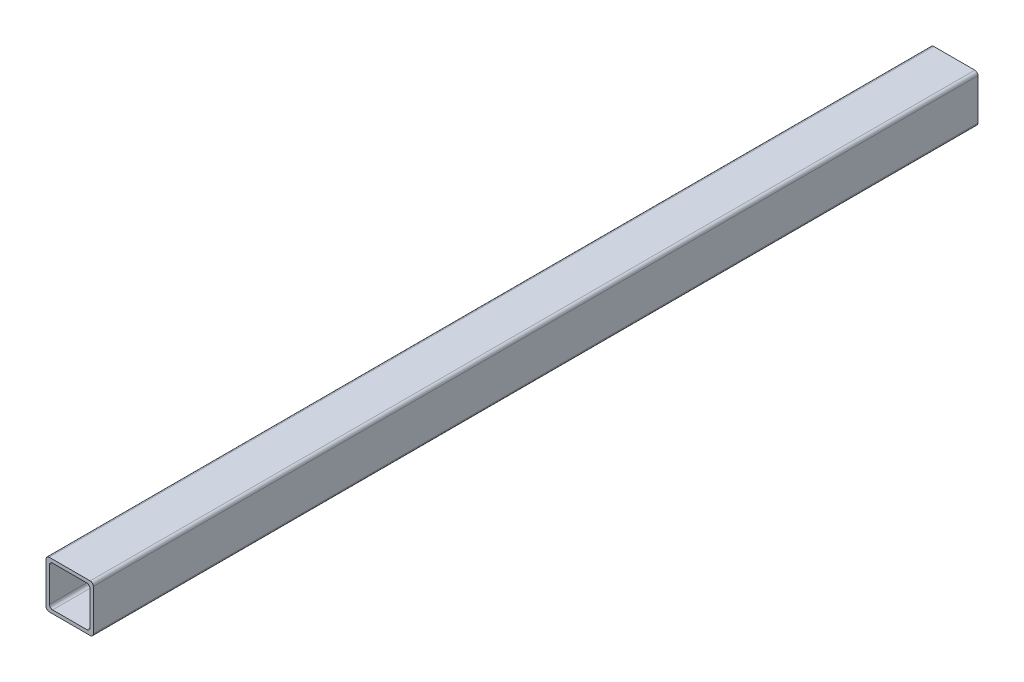
SolidWorks part; units mm, degrees
material "ASTM A500 Grade B"
ref_plane "Front Plane" through (0, 0, 0) normal (0, 0, 1) x (1, 0, 0)
ref_plane "Top Plane" through (0, 0, 0) normal (0, 1, 0) x (1, 0, 0)
ref_plane "Right Plane" through (0, 0, 0) normal (1, 0, 0) x (0, 0, -1)
sketch "Sketch1" plane through (0, 0, 0) normal (0, 0, 1) x (1, 0, 0)
  line L0 (5.3086, -2.7686) -> (32.7914, -2.7686)
  line L1 (2.54, 0) -> (35.56, 0)
  line L2 (0, -2.54) -> (0, -35.56)
  line L3 (2.54, -38.1) -> (35.56, -38.1)
  line L4 (38.1, -2.54) -> (38.1, -35.56)
  line L5 (35.3314, -5.3086) -> (35.3314, -32.7914)
  line L6 (5.3086, -35.3314) -> (32.7914, -35.3314)
  line L7 (2.7686, -5.3086) -> (2.7686, -32.7914)
  line L8 (0, 0) -> (0, -38.1) construction
  line L9 (0, -38.1) -> (38.1, -38.1) construction
  line L10 (38.1, 0) -> (38.1, -38.1) construction
  line L11 (2.7686, -2.7686) -> (2.7686, -35.3314) construction
  line L12 (2.7686, -35.3314) -> (35.3314, -35.3314) construction
  line L13 (35.3314, -2.7686) -> (35.3314, -35.3314) construction
  line L14 (2.7686, -2.7686) -> (35.3314, -2.7686) construction
  line L15 (0, 0) -> (38.1, 0) construction
  arc A0 (0, -35.56) -> (2.54, -38.1) centre (2.54, -35.56) ccw
  arc A1 (38.1, -35.56) -> (35.56, -38.1) centre (35.56, -35.56) cw
  arc A2 (2.7686, -32.7914) -> (5.3086, -35.3314) centre (5.3086, -32.7914) ccw
  arc A3 (32.7914, -35.3314) -> (35.3314, -32.7914) centre (32.7914, -32.7914) ccw
  arc A4 (35.3314, -5.3086) -> (32.7914, -2.7686) centre (32.7914, -5.3086) ccw
  arc A5 (38.1, -2.54) -> (35.56, 0) centre (35.56, -2.54) ccw
  arc A6 (0, -2.54) -> (2.54, 0) centre (2.54, -2.54) cw
  arc A7 (5.3086, -2.7686) -> (2.7686, -5.3086) centre (5.3086, -5.3086) ccw
  point P12 (0, -38.1)
  dimension "D4" = 2.54
  dimension "D3" = 2.7686
extrude "Boss-Extrude1" add sketch "Sketch1" along normal blind 737
sketch "Sketch2" plane through (0, 0, 0) normal (0, 1, 0) x (1, 0, 0)
  line L0 (0, -737) -> (0, 0) construction
  line L1 (0, -711.9) -> (38.1, -711.9)
  line L2 (0, -711.9) -> (0, -737)
  line L3 (0, -737) -> (38.1, -737)
  line L4 (38.1, -711.9) -> (38.1, -737)
  line L5 (-3924.1, -711.9) -> (1319.7, -711.9) construction
extrude "Cut-Extrude1" cut sketch "Sketch2" against normal through all
